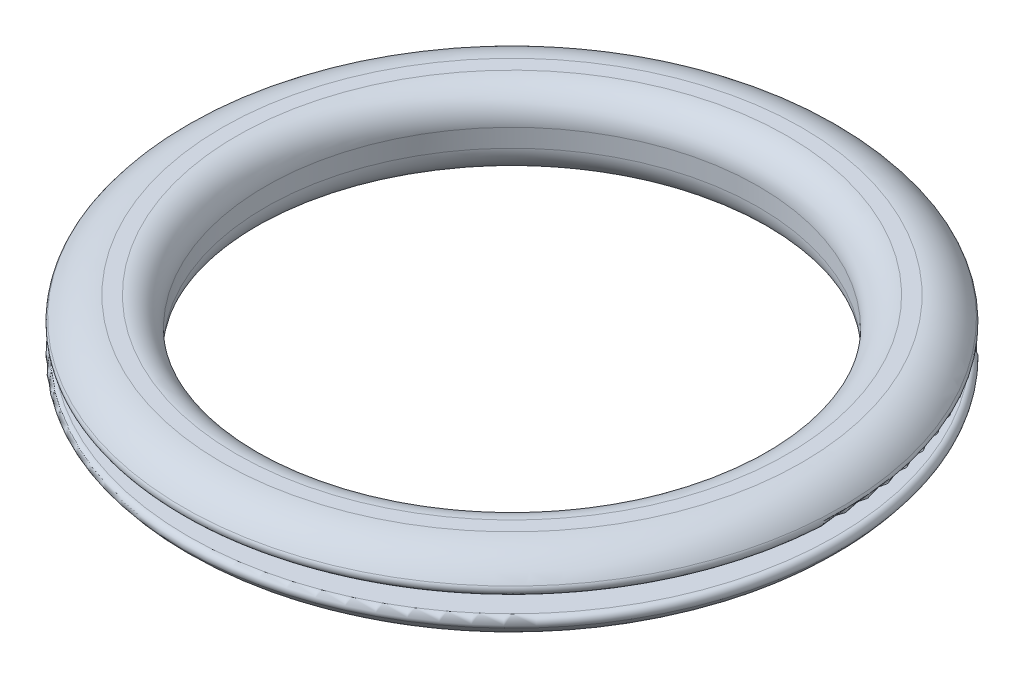
SolidWorks part; units mm, degrees
ref_plane "Front Plane" through (0, 0, 0) normal (0, 0, 1) x (1, 0, 0)
ref_plane "Top Plane" through (0, 0, 0) normal (0, 1, 0) x (1, 0, 0)
ref_plane "Right Plane" through (0, 0, 0) normal (1, 0, 0) x (0, 0, -1)
sketch "Sketch1" plane through (0, 0, 0) normal (0, 0, 1) x (1, 0, 0)
  line L5 (0, 0) -> (50425.861, 0) construction
  line L9 (21.59, 3.3337) -> (21.59, -3.3337)
  line L10 (21.59, -3.3337) -> (25.4, -3.3337)
  line L11 (29.21, -0.7938) -> (25.4, -0.7938)
  line L12 (25.4, -0.7938) -> (25.4, 0.7938)
  line L13 (29.21, 0.7938) -> (25.4, 0.7938)
  line L14 (21.59, 3.3337) -> (25.4, 3.3337)
  line L15 (0, 0) -> (0, 50425.861) construction
  line L16 (29.21, -0.7938) -> (29.21, -3.6911) construction
  arc A2 (25.4, -3.3337) -> (29.21, -0.7938) centre (25.4, 0.7938) ccw
  arc A3 (25.4, 3.3337) -> (29.21, 0.7938) centre (25.4, -0.7938) cw
  point P10 (0, 0)
  dimension "D1" = 50.8
  dimension "D2" = 1.5875
  dimension "D3" = 3.81
  dimension "D4" = 3.81
  dimension "D5" = 2.54
revolve "Revolve1" add sketch "Sketch1" angle 360 about L15
fillet "Fillet1" radius 2.54 2 edges at (0, -3.3337, -21.59) (0, 3.3337, -21.59)
fillet "Fillet2" radius 0.508 2 edges at (0, -0.7938, -29.21) (0, 0.7938, -29.21)
